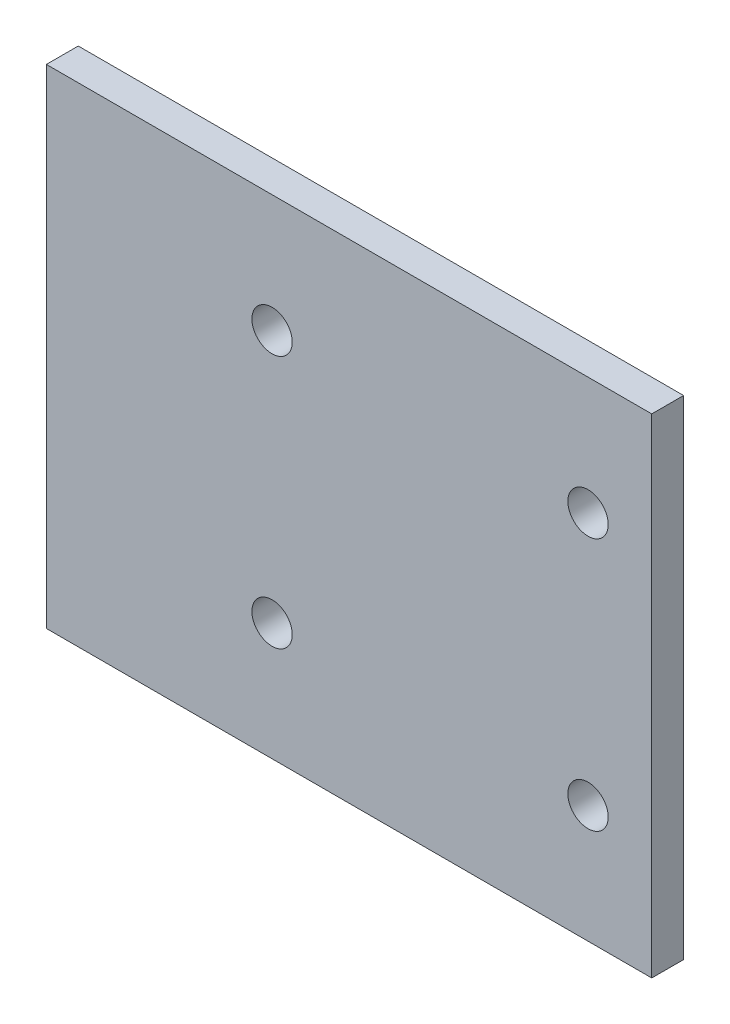
SolidWorks part; units mm, degrees
material "Oak"
ref_plane "Front Plane" through (0, 0, 0) normal (0, 0, 1) x (1, 0, 0)
ref_plane "Top Plane" through (0, 0, 0) normal (0, 1, 0) x (1, 0, 0)
ref_plane "Right Plane" through (0, 0, 0) normal (1, 0, 0) x (0, 0, -1)
sketch "Sketch1" plane through (0, 0, 0) normal (0, 0, 1) x (1, 0, 0)
  line L1 (-36.0143, 24.5902) -> (20.9857, 24.5902)
  line L2 (-36.0143, 24.5902) -> (-36.0143, -21.4098)
  line L3 (-36.0143, -21.4098) -> (20.9857, -21.4098)
  line L4 (20.9857, 24.5902) -> (20.9857, -21.4098)
  dimension "D1" = 46
  dimension "D2" = 57
extrude "Boss-Extrude1" add sketch "Sketch1" along normal blind 3
hole_wizard "#6 Clearance Hole1" positions "Sketch2" profile "Sketch3" hole size "#6" standard "ANSI Inch" end condition through all
sketch "Sketch2" plane through (0, 0, 3) normal (0, 0, 1) x (1, 0, 0)
  line L0 (20.9857, -21.4098) -> (20.9857, 24.5902) construction
  line L1 (20.9857, 24.5902) -> (-36.0143, 24.5902) construction
  line L2 (-36.0143, -21.4098) -> (20.9857, -21.4098) construction
  point P0 (14.9857, 13.5152)
  point P2 (14.9857, -10.3348)
  point P4 (-14.7643, -10.3348)
  point P6 (-14.7643, 13.5152)
  point P9 (0, 0)
  point P10 (0, 0)
  dimension "D1" = 29.75
  dimension "D2" = 29.75
  dimension "D3" = 23.85
  dimension "D4" = 23.85
  dimension "D5" = 6
  dimension "D6" = 11.075
  dimension "D7" = 6
  dimension "D8" = 11.075
sketch "Sketch3" plane through (14.9857, 13.5152, 3) normal (1, 0, 0) x (0, -1, 0)
  line L0 (0, 0) -> (0, 3)
  line L1 (0, 3) -> (1.8986, 3)
  line L2 (1.8986, 3) -> (1.8986, 0)
  line L5 (1.8986, 0) -> (0, 0)
  line L11 (0, -6.35) -> (0, 107.95) construction
  dimension "Thru Hole Dia." = 3.7973
  dimension "Thru Hole Depth" = 3
